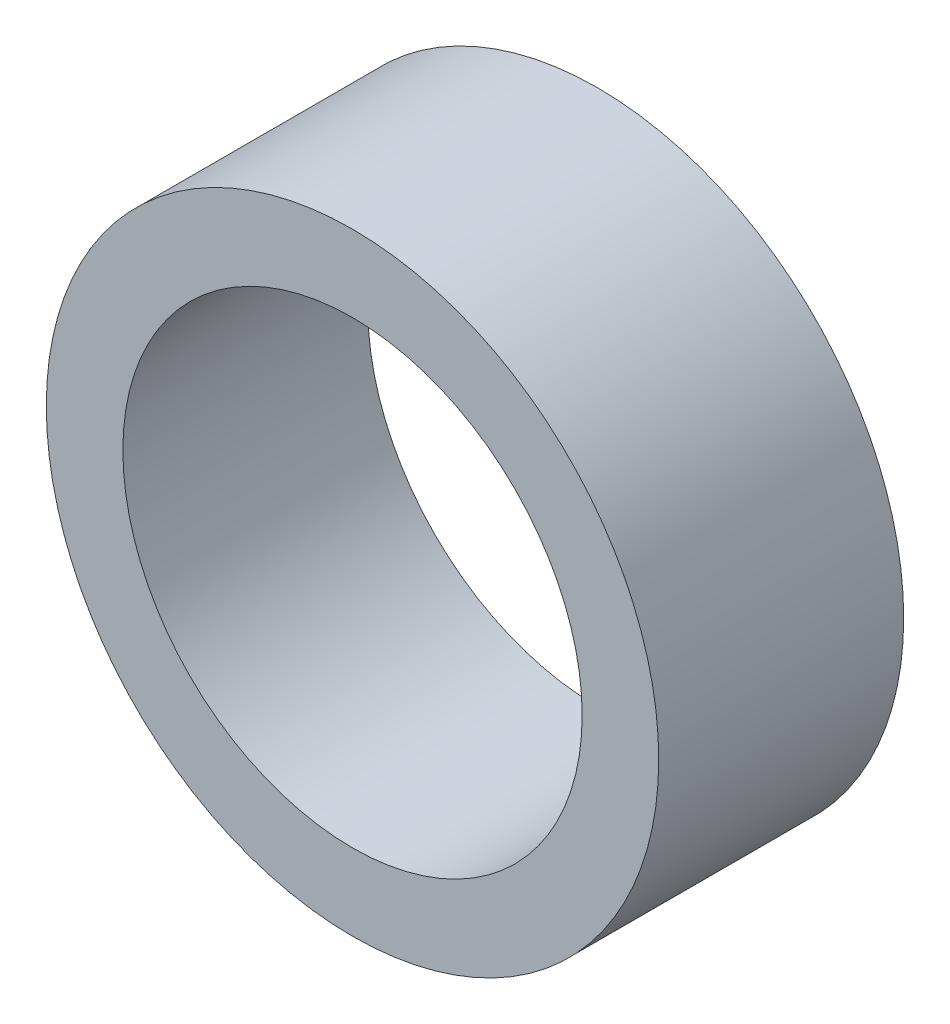
SolidWorks part; units mm, degrees
ref_plane "前视基准面" through (0, 0, 0) normal (0, 0, 1) x (1, 0, 0)
ref_plane "上视基准面" through (0, 0, 0) normal (0, 1, 0) x (1, 0, 0)
ref_plane "右视基准面" through (0, 0, 0) normal (1, 0, 0) x (0, 0, -1)
other "Configuration Table"
sketch "草图1" plane through (0, 0, 0) normal (0, 0, 1) x (1, 0, 0)
  circle A0 centre (0, 0) radius 4
  circle A1 centre (0, 0) radius 3
  dimension "D1" = 6
  dimension "D2" = 8
extrude "凸台-拉伸1" add sketch "草图1" along normal blind 3.2
